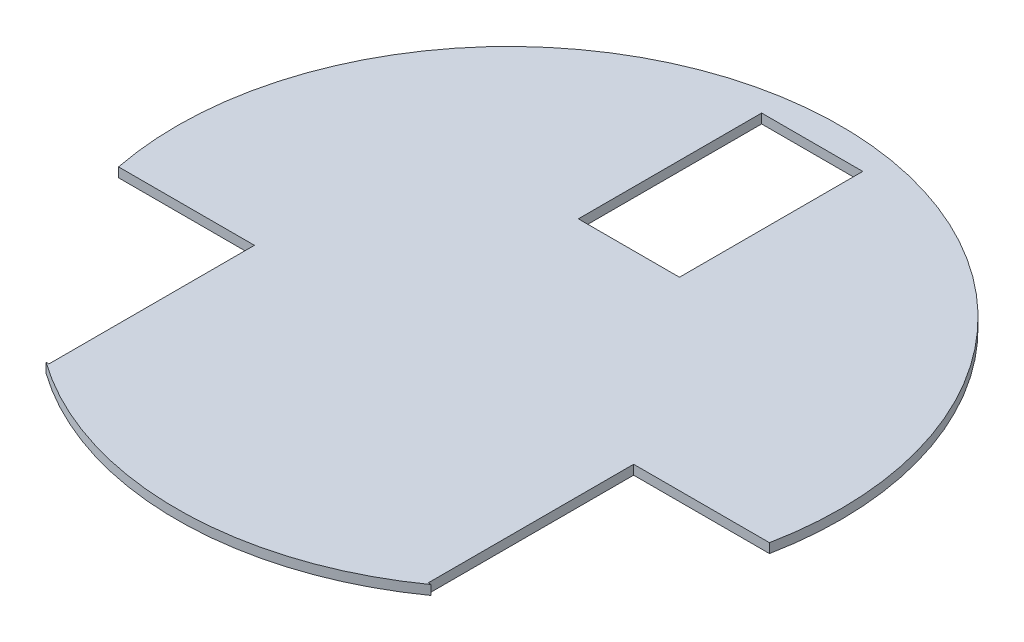
SolidWorks part; units mm, degrees
ref_plane "前视基准面" through (0, 0, 0) normal (0, 0, 1) x (1, 0, 0)
ref_plane "上视基准面" through (0, 0, 0) normal (0, 1, 0) x (1, 0, 0)
ref_plane "右视基准面" through (0, 0, 0) normal (1, 0, 0) x (0, 0, -1)
sketch "草图1" plane through (0, 0, 0) normal (0, 1, 0) x (1, 0, 0)
  circle A0 centre (0, 0) radius 105
  dimension "D1" = 210
extrude "原型底盘" add sketch "草图1" along normal blind 3
sketch "草图5" plane through (0, 3, 0) normal (0, 1, 0) x (1, 0, 0)
  line L0 (0, 0) -> (0, -20)
  line L1 (-105, -20.5) -> (-60, -20.5)
  line L2 (-105, -20.5) -> (-105, -85.5)
  line L3 (-105, -85.5) -> (-60, -85.5)
  line L4 (-60, -20.5) -> (-60, -85.5)
  line L5 (60, -20.5) -> (60, -85.5)
  line L6 (105, -85.5) -> (60, -85.5)
  line L7 (105, -20.5) -> (105, -85.5)
  line L8 (105, -20.5) -> (60, -20.5)
  point P4 (-60, -53)
  circle M4 centre (0, 0) radius 105
  dimension "D1" = 53
  dimension "D2" = 65
  dimension "D3" = 120
  dimension "D4" = 45
extrude "后轮空位" cut sketch "草图5" against normal through all contours L4 L1 L3 M4 | L8 L5 L6 M4
sketch "草图6" plane through (0, 3, 0) normal (0, 1, 0) x (1, 0, 0)
  line L1 (-16, 96) -> (16, 96)
  line L2 (-16, 96) -> (-16, 38)
  line L3 (-16, 38) -> (16, 38)
  line L4 (16, 96) -> (16, 38)
  point P4 (0, 38)
  point P6 (16, 67)
  dimension "D1" = 0
  dimension "D2" = 32
  dimension "D3" = 58
  dimension "D4" = 67
extrude "前轮空位" cut sketch "草图6" against normal through all
